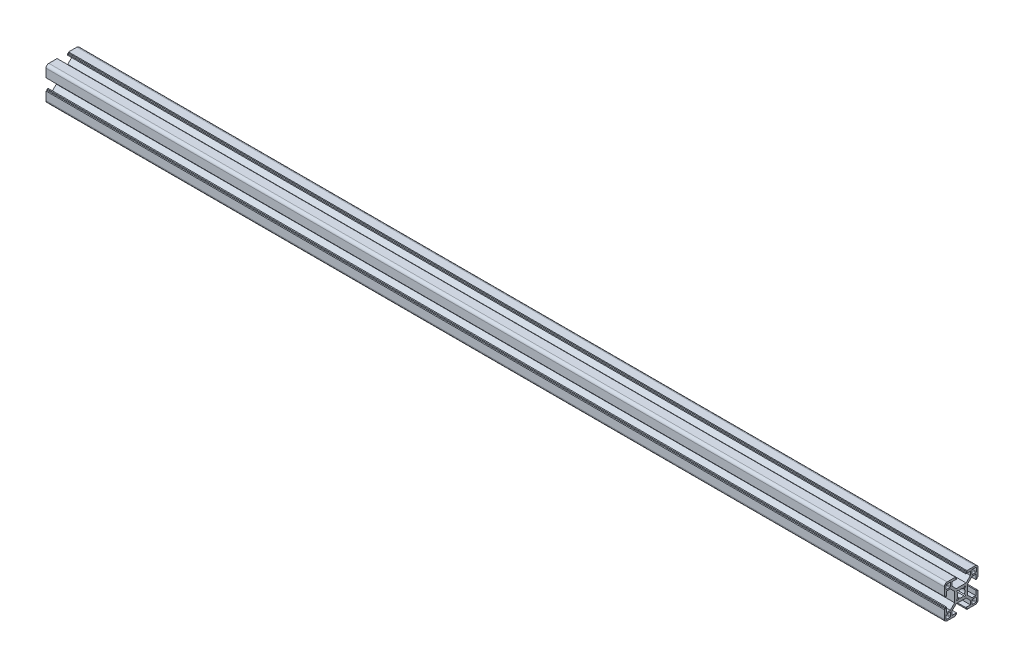
SolidWorks part; units mm, degrees
ref_plane "前视基准面" through (0, 0, 0) normal (0, 0, 1) x (1, 0, 0)
ref_plane "上视基准面" through (0, 0, 0) normal (0, 1, 0) x (1, 0, 0)
ref_plane "右视基准面" through (0, 0, 0) normal (1, 0, 0) x (0, 0, -1)
other "Configuration Table"
sketch "草图1" plane through (0, 0, 0) normal (1, 0, 0) x (0, 0, -1)
  line L0 (-5.1496, -13.7047) -> (-4.1496, -13.7047)
  line L1 (-4.1496, -13.7047) -> (-4.1496, -12.7047)
  line L2 (-4.1496, -12.7047) -> (-8.2996, -12.7047)
  line L3 (-8.2996, -12.7047) -> (-8.2996, -9.3689)
  line L4 (-8.2996, -9.3689) -> (-4.4354, -5.5047)
  line L5 (-4.4354, -5.5047) -> (4.3362, -5.5047)
  line L6 (4.3362, -5.5047) -> (8.2004, -9.3689)
  line L7 (8.2004, -9.3689) -> (8.2004, -12.7047)
  line L8 (8.2004, -12.7047) -> (4.0504, -12.7047)
  line L9 (4.0504, -12.7047) -> (4.0504, -13.7047)
  line L10 (4.0504, -13.7047) -> (5.0504, -13.7047)
  line L11 (5.0504, -13.7047) -> (5.0504, -14.7047)
  line L12 (5.0504, -14.7047) -> (12.4504, -14.7047)
  line L13 (14.9504, -12.2047) -> (14.9504, -4.8047)
  line L14 (14.9504, -4.8047) -> (13.9504, -4.8047)
  line L15 (13.9504, -4.8047) -> (13.9504, -3.8047)
  line L16 (13.9504, -3.8047) -> (12.9504, -3.8047)
  line L17 (12.9504, -3.8047) -> (12.9504, -7.9547)
  line L18 (12.9504, -7.9547) -> (9.6146, -7.9547)
  line L19 (9.6146, -7.9547) -> (5.7504, -4.0905)
  line L20 (5.7504, -4.0905) -> (5.7504, 4.6811)
  line L21 (5.7504, 4.6811) -> (9.6146, 8.5453)
  line L22 (9.6146, 8.5453) -> (12.9504, 8.5453)
  line L23 (12.9504, 8.5453) -> (12.9504, 4.3953)
  line L24 (12.9504, 4.3953) -> (13.9504, 4.3953)
  line L25 (13.9504, 4.3953) -> (13.9504, 5.3953)
  line L26 (13.9504, 5.3953) -> (14.9504, 5.3953)
  line L27 (14.9504, 5.3953) -> (14.9504, 12.7953)
  line L28 (12.4504, 15.2953) -> (5.0504, 15.2953)
  line L29 (5.0504, 15.2953) -> (5.0504, 14.2953)
  line L30 (5.0504, 14.2953) -> (4.0504, 14.2953)
  line L31 (4.0504, 14.2953) -> (4.0504, 13.2953)
  line L32 (4.0504, 13.2953) -> (8.2004, 13.2953)
  line L33 (8.2004, 13.2953) -> (8.2004, 9.9595)
  line L34 (8.2004, 9.9595) -> (4.3362, 6.0953)
  line L35 (4.3362, 6.0953) -> (-4.4354, 6.0953)
  line L36 (-4.4354, 6.0953) -> (-8.2996, 9.9595)
  line L37 (-8.2996, 9.9595) -> (-8.2996, 13.2953)
  line L38 (-8.2996, 13.2953) -> (-4.1496, 13.2953)
  line L39 (-4.1496, 13.2953) -> (-4.1496, 14.2953)
  line L40 (-4.1496, 14.2953) -> (-5.1496, 14.2953)
  line L41 (-5.1496, 14.2953) -> (-5.1496, 15.2953)
  line L42 (-5.1496, 15.2953) -> (-12.5496, 15.2953)
  line L43 (-15.0496, 12.7953) -> (-15.0496, 5.3953)
  line L44 (-15.0496, 5.3953) -> (-14.0496, 5.3953)
  line L45 (-14.0496, 5.3953) -> (-14.0496, 4.3953)
  line L46 (-14.0496, 4.3953) -> (-13.0496, 4.3953)
  line L47 (-13.0496, 4.3953) -> (-13.0496, 8.5453)
  line L48 (-13.0496, 8.5453) -> (-9.7138, 8.5453)
  line L49 (-9.7138, 8.5453) -> (-5.8496, 4.6811)
  line L50 (-5.8496, 4.6811) -> (-5.8496, -4.0905)
  line L51 (-5.8496, -4.0905) -> (-9.7138, -7.9547)
  line L52 (-9.7138, -7.9547) -> (-13.0496, -7.9547)
  line L53 (-13.0496, -7.9547) -> (-13.0496, -3.8047)
  line L54 (-13.0496, -3.8047) -> (-14.0496, -3.8047)
  line L55 (-14.0496, -3.8047) -> (-14.0496, -4.8047)
  line L56 (-14.0496, -4.8047) -> (-15.0496, -4.8047)
  line L57 (-15.0496, -4.8047) -> (-15.0496, -12.2047)
  line L58 (-12.5496, -14.7047) -> (-5.1496, -14.7047)
  line L59 (-5.1496, -14.7047) -> (-5.1496, -13.7047)
  line L60 (-10.0496, 9.7953) -> (-13.0496, 9.7953)
  line L61 (-13.5496, 10.2953) -> (-13.5496, 13.2953)
  line L62 (-13.0496, 13.7953) -> (-10.0496, 13.7953)
  line L63 (-9.5496, 13.2953) -> (-9.5496, 10.2953)
  line L64 (-10.0496, -13.2047) -> (-13.0496, -13.2047)
  line L65 (-13.5496, -12.7047) -> (-13.5496, -9.7047)
  line L66 (-13.0496, -9.2047) -> (-10.0496, -9.2047)
  line L67 (-9.5496, -9.7047) -> (-9.5496, -12.7047)
  line L68 (12.9504, 9.7953) -> (9.9504, 9.7953)
  line L69 (9.4504, 10.2953) -> (9.4504, 13.2953)
  line L70 (9.9504, 13.7953) -> (12.9504, 13.7953)
  line L71 (13.4504, 13.2953) -> (13.4504, 10.2953)
  line L72 (13.4504, -9.7047) -> (13.4504, -12.7047)
  line L73 (12.9504, -13.2047) -> (9.9504, -13.2047)
  line L74 (9.4504, -12.7047) -> (9.4504, -9.7047)
  line L75 (9.9504, -9.2047) -> (12.9504, -9.2047)
  line L76 (-4.08, 3.6186) -> (-3.3729, 4.3257)
  line L77 (-3.3729, 4.3257) -> (-2.074, 3.0269)
  line L78 (1.9749, 3.0269) -> (3.2737, 4.3257)
  line L79 (3.2737, 4.3257) -> (3.9808, 3.6186)
  line L80 (3.9808, 3.6186) -> (2.682, 2.3198)
  line L81 (2.682, -1.7291) -> (3.9808, -3.028)
  line L82 (3.9808, -3.028) -> (3.2737, -3.7351)
  line L83 (3.2737, -3.7351) -> (1.9749, -2.4362)
  line L84 (-2.074, -2.4362) -> (-3.3729, -3.7351)
  line L85 (-3.3729, -3.7351) -> (-4.08, -3.028)
  line L86 (-4.08, -3.028) -> (-2.7811, -1.7291)
  line L87 (-2.7811, 2.3198) -> (-4.08, 3.6186)
  arc A0 (12.4504, -14.7047) -> (14.9504, -12.2047) centre (12.4504, -12.2047) ccw
  arc A1 (14.9504, 12.7953) -> (12.4504, 15.2953) centre (12.4504, 12.7953) ccw
  arc A2 (-12.5496, 15.2953) -> (-15.0496, 12.7953) centre (-12.5496, 12.7953) ccw
  arc A3 (-15.0496, -12.2047) -> (-12.5496, -14.7047) centre (-12.5496, -12.2047) ccw
  arc A4 (-9.5496, 10.2953) -> (-10.0496, 9.7953) centre (-10.0496, 10.2953) cw
  arc A5 (-13.0496, 9.7953) -> (-13.5496, 10.2953) centre (-13.0496, 10.2953) cw
  arc A6 (-13.5496, 13.2953) -> (-13.0496, 13.7953) centre (-13.0496, 13.2953) cw
  arc A7 (-10.0496, 13.7953) -> (-9.5496, 13.2953) centre (-10.0496, 13.2953) cw
  arc A8 (-9.5496, -12.7047) -> (-10.0496, -13.2047) centre (-10.0496, -12.7047) cw
  arc A9 (-13.0496, -13.2047) -> (-13.5496, -12.7047) centre (-13.0496, -12.7047) cw
  arc A10 (-13.5496, -9.7047) -> (-13.0496, -9.2047) centre (-13.0496, -9.7047) cw
  arc A11 (-10.0496, -9.2047) -> (-9.5496, -9.7047) centre (-10.0496, -9.7047) cw
  arc A12 (13.4504, 10.2953) -> (12.9504, 9.7953) centre (12.9504, 10.2953) cw
  arc A13 (9.9504, 9.7953) -> (9.4504, 10.2953) centre (9.9504, 10.2953) cw
  arc A14 (9.4504, 13.2953) -> (9.9504, 13.7953) centre (9.9504, 13.2953) cw
  arc A15 (12.9504, 13.7953) -> (13.4504, 13.2953) centre (12.9504, 13.2953) cw
  arc A16 (12.9504, -9.2047) -> (13.4504, -9.7047) centre (12.9504, -9.7047) cw
  arc A17 (13.4504, -12.7047) -> (12.9504, -13.2047) centre (12.9504, -12.7047) cw
  arc A18 (9.9504, -13.2047) -> (9.4504, -12.7047) centre (9.9504, -12.7047) cw
  arc A19 (9.4504, -9.7047) -> (9.9504, -9.2047) centre (9.9504, -9.7047) cw
  arc A20 (-2.074, 3.0269) -> (1.9749, 3.0269) centre (-0.0496, 0.2953) cw
  arc A21 (2.682, 2.3198) -> (2.682, -1.7291) centre (-0.0496, 0.2953) cw
  arc A22 (1.9749, -2.4362) -> (-2.074, -2.4362) centre (-0.0496, 0.2953) cw
  arc A23 (-2.7811, -1.7291) -> (-2.7811, 2.3198) centre (-0.0496, 0.2953) cw
extrude "凸台-拉伸1" add sketch "草图1" against normal blind 50
sketch "草图2" plane through (0, 0, 0) normal (1, 0, 0) x (0, 0, -1)
  line L4 (-13.0496, 9.7953) -> (-10.0496, 9.7953)
  line L5 (-13.5496, 13.2953) -> (-13.5496, 10.2953)
  line L6 (-10.0496, 13.7953) -> (-13.0496, 13.7953)
  line L7 (-9.5496, 10.2953) -> (-9.5496, 13.2953)
  line L8 (-13.0496, 9.7953) -> (-10.0496, 9.7953)
  line L9 (-13.5496, 13.2953) -> (-13.5496, 10.2953)
  line L10 (-10.0496, 13.7953) -> (-13.0496, 13.7953)
  line L11 (-9.5496, 10.2953) -> (-9.5496, 13.2953)
  line L12 (-13.0496, -13.2047) -> (-10.0496, -13.2047)
  line L13 (-13.5496, -9.7047) -> (-13.5496, -12.7047)
  line L14 (-10.0496, -9.2047) -> (-13.0496, -9.2047)
  line L15 (-9.5496, -12.7047) -> (-9.5496, -9.7047)
  line L16 (-13.0496, -13.2047) -> (-10.0496, -13.2047)
  line L17 (-13.5496, -9.7047) -> (-13.5496, -12.7047)
  line L18 (-10.0496, -9.2047) -> (-13.0496, -9.2047)
  line L19 (-9.5496, -12.7047) -> (-9.5496, -9.7047)
  line L20 (9.4504, 13.2953) -> (9.4504, 10.2953)
  line L21 (12.9504, 13.7953) -> (9.9504, 13.7953)
  line L22 (13.4504, 10.2953) -> (13.4504, 13.2953)
  line L23 (9.9504, 9.7953) -> (12.9504, 9.7953)
  line L24 (9.4504, 13.2953) -> (9.4504, 10.2953)
  line L25 (12.9504, 13.7953) -> (9.9504, 13.7953)
  line L26 (13.4504, 10.2953) -> (13.4504, 13.2953)
  line L27 (9.9504, 9.7953) -> (12.9504, 9.7953)
  line L28 (9.4504, -9.7047) -> (9.4504, -12.7047)
  line L29 (12.9504, -9.2047) -> (9.9504, -9.2047)
  line L30 (13.4504, -12.7047) -> (13.4504, -9.7047)
  line L31 (9.9504, -13.2047) -> (12.9504, -13.2047)
  line L32 (9.4504, -9.7047) -> (9.4504, -12.7047)
  line L33 (12.9504, -9.2047) -> (9.9504, -9.2047)
  line L34 (13.4504, -12.7047) -> (13.4504, -9.7047)
  line L35 (9.9504, -13.2047) -> (12.9504, -13.2047)
  line L44 (-3.3729, -3.7351) -> (-2.074, -2.4362)
  line L45 (-4.08, -3.028) -> (-3.3729, -3.7351)
  line L46 (-2.7811, -1.7291) -> (-4.08, -3.028)
  line L47 (-4.08, 3.6186) -> (-2.7811, 2.3198)
  line L48 (-3.3729, 4.3257) -> (-4.08, 3.6186)
  line L49 (-2.074, 3.0269) -> (-3.3729, 4.3257)
  line L50 (3.2737, 4.3257) -> (1.9749, 3.0269)
  line L51 (3.9808, 3.6186) -> (3.2737, 4.3257)
  line L52 (2.682, 2.3198) -> (3.9808, 3.6186)
  line L53 (3.9808, -3.028) -> (2.682, -1.7291)
  line L54 (3.2737, -3.7351) -> (3.9808, -3.028)
  line L55 (1.9749, -2.4362) -> (3.2737, -3.7351)
  line L56 (-3.3729, -3.7351) -> (-2.074, -2.4362)
  line L57 (-4.08, -3.028) -> (-3.3729, -3.7351)
  line L58 (-2.7811, -1.7291) -> (-4.08, -3.028)
  line L59 (-4.08, 3.6186) -> (-2.7811, 2.3198)
  line L60 (-3.3729, 4.3257) -> (-4.08, 3.6186)
  line L61 (-2.074, 3.0269) -> (-3.3729, 4.3257)
  line L62 (3.2737, 4.3257) -> (1.9749, 3.0269)
  line L63 (3.9808, 3.6186) -> (3.2737, 4.3257)
  line L64 (2.682, 2.3198) -> (3.9808, 3.6186)
  line L65 (3.9808, -3.028) -> (2.682, -1.7291)
  line L66 (3.2737, -3.7351) -> (3.9808, -3.028)
  line L67 (1.9749, -2.4362) -> (3.2737, -3.7351)
  line L68 (-15.0496, -4.8047) -> (-15.0496, -12.2047)
  line L69 (-14.0496, -4.8047) -> (-15.0496, -4.8047)
  line L70 (-14.0496, -3.8047) -> (-14.0496, -4.8047)
  line L71 (-13.0496, -3.8047) -> (-14.0496, -3.8047)
  line L72 (-13.0496, -7.9547) -> (-13.0496, -3.8047)
  line L73 (-9.7138, -7.9547) -> (-13.0496, -7.9547)
  line L74 (-5.8496, -4.0905) -> (-9.7138, -7.9547)
  line L75 (-5.8496, 4.6811) -> (-5.8496, -4.0905)
  line L76 (-9.7138, 8.5453) -> (-5.8496, 4.6811)
  line L77 (-13.0496, 8.5453) -> (-9.7138, 8.5453)
  line L78 (-13.0496, 4.3953) -> (-13.0496, 8.5453)
  line L79 (-14.0496, 4.3953) -> (-13.0496, 4.3953)
  line L80 (-14.0496, 5.3953) -> (-14.0496, 4.3953)
  line L81 (-15.0496, 5.3953) -> (-14.0496, 5.3953)
  line L82 (-15.0496, 12.7953) -> (-15.0496, 5.3953)
  line L83 (-5.1496, 15.2953) -> (-12.5496, 15.2953)
  line L84 (-5.1496, 14.2953) -> (-5.1496, 15.2953)
  line L85 (-4.1496, 14.2953) -> (-5.1496, 14.2953)
  line L86 (-4.1496, 13.2953) -> (-4.1496, 14.2953)
  line L87 (-8.2996, 13.2953) -> (-4.1496, 13.2953)
  line L88 (-8.2996, 9.9595) -> (-8.2996, 13.2953)
  line L89 (-4.4354, 6.0953) -> (-8.2996, 9.9595)
  line L90 (4.3362, 6.0953) -> (-4.4354, 6.0953)
  line L91 (8.2004, 9.9595) -> (4.3362, 6.0953)
  line L92 (8.2004, 13.2953) -> (8.2004, 9.9595)
  line L93 (4.0504, 13.2953) -> (8.2004, 13.2953)
  line L94 (4.0504, 14.2953) -> (4.0504, 13.2953)
  line L95 (5.0504, 14.2953) -> (4.0504, 14.2953)
  line L96 (5.0504, 15.2953) -> (5.0504, 14.2953)
  line L97 (12.4504, 15.2953) -> (5.0504, 15.2953)
  line L98 (14.9504, 5.3953) -> (14.9504, 12.7953)
  line L99 (13.9504, 5.3953) -> (14.9504, 5.3953)
  line L100 (13.9504, 4.3953) -> (13.9504, 5.3953)
  line L101 (12.9504, 4.3953) -> (13.9504, 4.3953)
  line L102 (12.9504, 8.5453) -> (12.9504, 4.3953)
  line L103 (9.6146, 8.5453) -> (12.9504, 8.5453)
  line L104 (5.7504, 4.6811) -> (9.6146, 8.5453)
  line L105 (5.7504, -4.0905) -> (5.7504, 4.6811)
  line L106 (9.6146, -7.9547) -> (5.7504, -4.0905)
  line L107 (12.9504, -7.9547) -> (9.6146, -7.9547)
  line L108 (12.9504, -3.8047) -> (12.9504, -7.9547)
  line L109 (13.9504, -3.8047) -> (12.9504, -3.8047)
  line L110 (13.9504, -4.8047) -> (13.9504, -3.8047)
  line L111 (14.9504, -4.8047) -> (13.9504, -4.8047)
  line L112 (14.9504, -12.2047) -> (14.9504, -4.8047)
  line L113 (5.0504, -14.7047) -> (12.4504, -14.7047)
  line L114 (5.0504, -13.7047) -> (5.0504, -14.7047)
  line L115 (4.0504, -13.7047) -> (5.0504, -13.7047)
  line L116 (4.0504, -12.7047) -> (4.0504, -13.7047)
  line L117 (8.2004, -12.7047) -> (4.0504, -12.7047)
  line L118 (8.2004, -9.3689) -> (8.2004, -12.7047)
  line L119 (4.3362, -5.5047) -> (8.2004, -9.3689)
  line L120 (-4.4354, -5.5047) -> (4.3362, -5.5047)
  line L121 (-8.2996, -9.3689) -> (-4.4354, -5.5047)
  line L122 (-8.2996, -12.7047) -> (-8.2996, -9.3689)
  line L123 (-4.1496, -12.7047) -> (-8.2996, -12.7047)
  line L124 (-4.1496, -13.7047) -> (-4.1496, -12.7047)
  line L125 (-5.1496, -13.7047) -> (-4.1496, -13.7047)
  line L126 (-5.1496, -14.7047) -> (-5.1496, -13.7047)
  line L127 (-12.5496, -14.7047) -> (-5.1496, -14.7047)
  line L128 (-15.0496, -4.8047) -> (-15.0496, -12.2047)
  line L129 (-14.0496, -4.8047) -> (-15.0496, -4.8047)
  line L130 (-14.0496, -3.8047) -> (-14.0496, -4.8047)
  line L131 (-13.0496, -3.8047) -> (-14.0496, -3.8047)
  line L132 (-13.0496, -7.9547) -> (-13.0496, -3.8047)
  line L133 (-9.7138, -7.9547) -> (-13.0496, -7.9547)
  line L134 (-5.8496, -4.0905) -> (-9.7138, -7.9547)
  line L135 (-5.8496, 4.6811) -> (-5.8496, -4.0905)
  line L136 (-9.7138, 8.5453) -> (-5.8496, 4.6811)
  line L137 (-13.0496, 8.5453) -> (-9.7138, 8.5453)
  line L138 (-13.0496, 4.3953) -> (-13.0496, 8.5453)
  line L139 (-14.0496, 4.3953) -> (-13.0496, 4.3953)
  line L140 (-14.0496, 5.3953) -> (-14.0496, 4.3953)
  line L141 (-15.0496, 5.3953) -> (-14.0496, 5.3953)
  line L142 (-15.0496, 12.7953) -> (-15.0496, 5.3953)
  line L143 (-5.1496, 15.2953) -> (-12.5496, 15.2953)
  line L144 (-5.1496, 14.2953) -> (-5.1496, 15.2953)
  line L145 (-4.1496, 14.2953) -> (-5.1496, 14.2953)
  line L146 (-4.1496, 13.2953) -> (-4.1496, 14.2953)
  line L147 (-8.2996, 13.2953) -> (-4.1496, 13.2953)
  line L148 (-8.2996, 9.9595) -> (-8.2996, 13.2953)
  line L149 (-4.4354, 6.0953) -> (-8.2996, 9.9595)
  line L150 (4.3362, 6.0953) -> (-4.4354, 6.0953)
  line L151 (8.2004, 9.9595) -> (4.3362, 6.0953)
  line L152 (8.2004, 13.2953) -> (8.2004, 9.9595)
  line L153 (4.0504, 13.2953) -> (8.2004, 13.2953)
  line L154 (4.0504, 14.2953) -> (4.0504, 13.2953)
  line L155 (5.0504, 14.2953) -> (4.0504, 14.2953)
  line L156 (5.0504, 15.2953) -> (5.0504, 14.2953)
  line L157 (12.4504, 15.2953) -> (5.0504, 15.2953)
  line L158 (14.9504, 5.3953) -> (14.9504, 12.7953)
  line L159 (13.9504, 5.3953) -> (14.9504, 5.3953)
  line L160 (13.9504, 4.3953) -> (13.9504, 5.3953)
  line L161 (12.9504, 4.3953) -> (13.9504, 4.3953)
  line L162 (12.9504, 8.5453) -> (12.9504, 4.3953)
  line L163 (9.6146, 8.5453) -> (12.9504, 8.5453)
  line L164 (5.7504, 4.6811) -> (9.6146, 8.5453)
  line L165 (5.7504, -4.0905) -> (5.7504, 4.6811)
  line L166 (9.6146, -7.9547) -> (5.7504, -4.0905)
  line L167 (12.9504, -7.9547) -> (9.6146, -7.9547)
  line L168 (12.9504, -3.8047) -> (12.9504, -7.9547)
  line L169 (13.9504, -3.8047) -> (12.9504, -3.8047)
  line L170 (13.9504, -4.8047) -> (13.9504, -3.8047)
  line L171 (14.9504, -4.8047) -> (13.9504, -4.8047)
  line L172 (14.9504, -12.2047) -> (14.9504, -4.8047)
  line L173 (5.0504, -14.7047) -> (12.4504, -14.7047)
  line L174 (5.0504, -13.7047) -> (5.0504, -14.7047)
  line L175 (4.0504, -13.7047) -> (5.0504, -13.7047)
  line L176 (4.0504, -12.7047) -> (4.0504, -13.7047)
  line L177 (8.2004, -12.7047) -> (4.0504, -12.7047)
  line L178 (8.2004, -9.3689) -> (8.2004, -12.7047)
  line L179 (4.3362, -5.5047) -> (8.2004, -9.3689)
  line L180 (-4.4354, -5.5047) -> (4.3362, -5.5047)
  line L181 (-8.2996, -9.3689) -> (-4.4354, -5.5047)
  line L182 (-8.2996, -12.7047) -> (-8.2996, -9.3689)
  line L183 (-4.1496, -12.7047) -> (-8.2996, -12.7047)
  line L184 (-4.1496, -13.7047) -> (-4.1496, -12.7047)
  line L185 (-5.1496, -13.7047) -> (-4.1496, -13.7047)
  line L186 (-5.1496, -14.7047) -> (-5.1496, -13.7047)
  line L187 (-12.5496, -14.7047) -> (-5.1496, -14.7047)
  arc A4 (-13.5496, 10.2953) -> (-13.0496, 9.7953) centre (-13.0496, 10.2953) ccw
  arc A5 (-13.0496, 13.7953) -> (-13.5496, 13.2953) centre (-13.0496, 13.2953) ccw
  arc A6 (-9.5496, 13.2953) -> (-10.0496, 13.7953) centre (-10.0496, 13.2953) ccw
  arc A7 (-10.0496, 9.7953) -> (-9.5496, 10.2953) centre (-10.0496, 10.2953) ccw
  arc A8 (-13.5496, 10.2953) -> (-13.0496, 9.7953) centre (-13.0496, 10.2953) ccw
  arc A9 (-13.0496, 13.7953) -> (-13.5496, 13.2953) centre (-13.0496, 13.2953) ccw
  arc A10 (-9.5496, 13.2953) -> (-10.0496, 13.7953) centre (-10.0496, 13.2953) ccw
  arc A11 (-10.0496, 9.7953) -> (-9.5496, 10.2953) centre (-10.0496, 10.2953) ccw
  arc A12 (-12.5496, 15.2953) -> (-15.0496, 12.7953) centre (-12.5496, 12.7953) ccw
  arc A13 (14.9504, 12.7953) -> (12.4504, 15.2953) centre (12.4504, 12.7953) ccw
  arc A14 (12.4504, -14.7047) -> (14.9504, -12.2047) centre (12.4504, -12.2047) ccw
  arc A15 (-15.0496, -12.2047) -> (-12.5496, -14.7047) centre (-12.5496, -12.2047) ccw
  arc A16 (-12.5496, 15.2953) -> (-15.0496, 12.7953) centre (-12.5496, 12.7953) ccw
  arc A17 (14.9504, 12.7953) -> (12.4504, 15.2953) centre (12.4504, 12.7953) ccw
  arc A18 (12.4504, -14.7047) -> (14.9504, -12.2047) centre (12.4504, -12.2047) ccw
  arc A19 (-15.0496, -12.2047) -> (-12.5496, -14.7047) centre (-12.5496, -12.2047) ccw
  arc A20 (-13.5496, -12.7047) -> (-13.0496, -13.2047) centre (-13.0496, -12.7047) ccw
  arc A21 (-13.0496, -9.2047) -> (-13.5496, -9.7047) centre (-13.0496, -9.7047) ccw
  arc A22 (-9.5496, -9.7047) -> (-10.0496, -9.2047) centre (-10.0496, -9.7047) ccw
  arc A23 (-10.0496, -13.2047) -> (-9.5496, -12.7047) centre (-10.0496, -12.7047) ccw
  arc A24 (-13.5496, -12.7047) -> (-13.0496, -13.2047) centre (-13.0496, -12.7047) ccw
  arc A25 (-13.0496, -9.2047) -> (-13.5496, -9.7047) centre (-13.0496, -9.7047) ccw
  arc A26 (-9.5496, -9.7047) -> (-10.0496, -9.2047) centre (-10.0496, -9.7047) ccw
  arc A27 (-10.0496, -13.2047) -> (-9.5496, -12.7047) centre (-10.0496, -12.7047) ccw
  arc A28 (9.9504, 13.7953) -> (9.4504, 13.2953) centre (9.9504, 13.2953) ccw
  arc A29 (13.4504, 13.2953) -> (12.9504, 13.7953) centre (12.9504, 13.2953) ccw
  arc A30 (12.9504, 9.7953) -> (13.4504, 10.2953) centre (12.9504, 10.2953) ccw
  arc A31 (9.4504, 10.2953) -> (9.9504, 9.7953) centre (9.9504, 10.2953) ccw
  arc A32 (9.9504, 13.7953) -> (9.4504, 13.2953) centre (9.9504, 13.2953) ccw
  arc A33 (13.4504, 13.2953) -> (12.9504, 13.7953) centre (12.9504, 13.2953) ccw
  arc A34 (12.9504, 9.7953) -> (13.4504, 10.2953) centre (12.9504, 10.2953) ccw
  arc A35 (9.4504, 10.2953) -> (9.9504, 9.7953) centre (9.9504, 10.2953) ccw
  arc A36 (9.9504, -9.2047) -> (9.4504, -9.7047) centre (9.9504, -9.7047) ccw
  arc A37 (13.4504, -9.7047) -> (12.9504, -9.2047) centre (12.9504, -9.7047) ccw
  arc A38 (12.9504, -13.2047) -> (13.4504, -12.7047) centre (12.9504, -12.7047) ccw
  arc A39 (9.4504, -12.7047) -> (9.9504, -13.2047) centre (9.9504, -12.7047) ccw
  arc A40 (9.9504, -9.2047) -> (9.4504, -9.7047) centre (9.9504, -9.7047) ccw
  arc A41 (13.4504, -9.7047) -> (12.9504, -9.2047) centre (12.9504, -9.7047) ccw
  arc A42 (12.9504, -13.2047) -> (13.4504, -12.7047) centre (12.9504, -12.7047) ccw
  arc A43 (9.4504, -12.7047) -> (9.9504, -13.2047) centre (9.9504, -12.7047) ccw
  arc A44 (-2.7811, 2.3198) -> (-2.7811, -1.7291) centre (-0.0496, 0.2953) ccw
  arc A45 (1.9749, 3.0269) -> (-2.074, 3.0269) centre (-0.0496, 0.2953) ccw
  arc A46 (2.682, -1.7291) -> (2.682, 2.3198) centre (-0.0496, 0.2953) ccw
  arc A47 (-2.074, -2.4362) -> (1.9749, -2.4362) centre (-0.0496, 0.2953) ccw
  arc A48 (-2.7811, 2.3198) -> (-2.7811, -1.7291) centre (-0.0496, 0.2953) ccw
  arc A49 (1.9749, 3.0269) -> (-2.074, 3.0269) centre (-0.0496, 0.2953) ccw
  arc A50 (2.682, -1.7291) -> (2.682, 2.3198) centre (-0.0496, 0.2953) ccw
  arc A51 (-2.074, -2.4362) -> (1.9749, -2.4362) centre (-0.0496, 0.2953) ccw
  dimension "D1" = 0
  dimension "D2" = 0
  dimension "D3" = 0
  dimension "D4" = 0
  dimension "D5" = 0
  dimension "D6" = 0
extrude "凸台-拉伸2" add sketch "草图2" against normal blind 800
